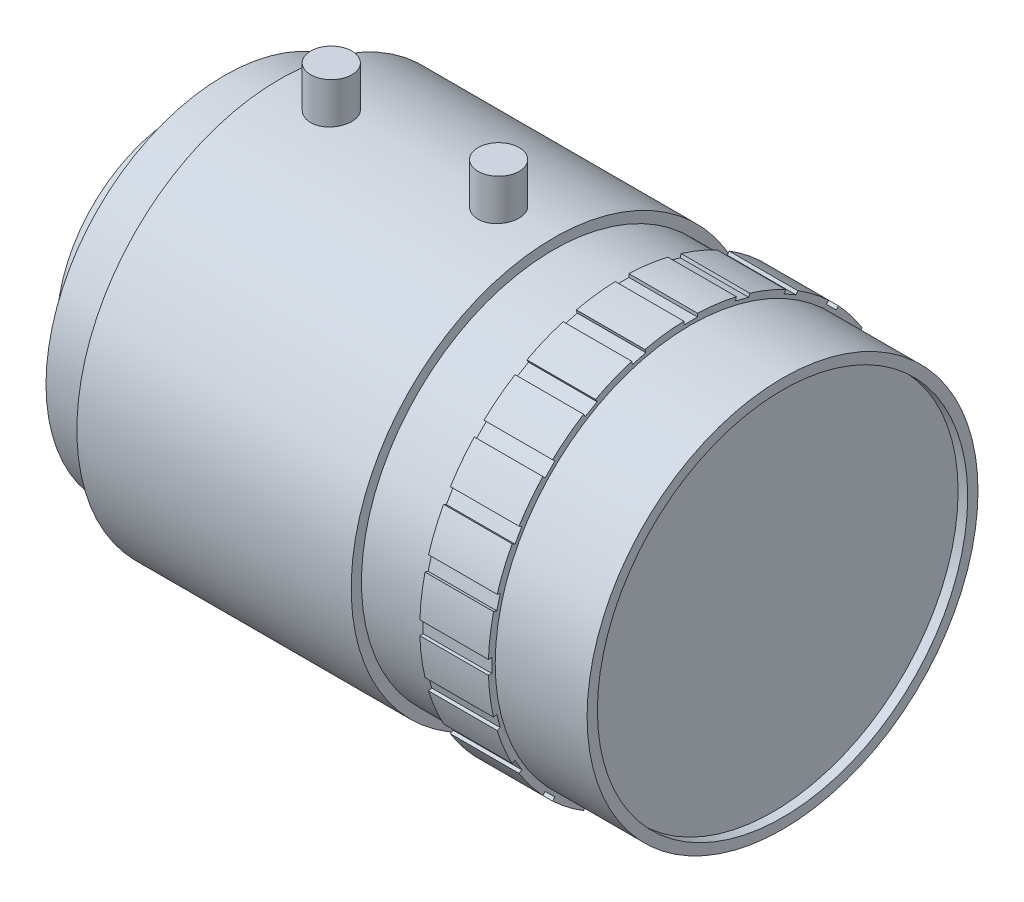
SolidWorks part; units mm, degrees
ref_plane "前视基准面" through (0, 0, 0) normal (0, 0, 1) x (1, 0, 0)
ref_plane "上视基准面" through (0, 0, 0) normal (0, 1, 0) x (1, 0, 0)
ref_plane "右视基准面" through (0, 0, 0) normal (1, 0, 0) x (0, 0, -1)
sketch "草图1" plane through (0, 0, 0) normal (1, 0, 0) x (0, 0, -1)
  circle A0 centre (0, 0) radius 14.75
  dimension "D1" = 29.5
extrude "凸台-拉伸1" add sketch "草图1" along normal blind 20
sketch "草图2" plane through (20, 0, 0) normal (1, 0, 0) x (0, 0, -1)
  circle A0 centre (0, 0) radius 14
  dimension "D1" = 28
extrude "凸台-拉伸2" add sketch "草图2" along normal blind 5
sketch "草图3" plane through (25, 0, 0) normal (1, 0, 0) x (0, 0, -1)
  circle A0 centre (0, 0) radius 14.75
extrude "凸台-拉伸3" add sketch "草图3" along normal blind 5
sketch "草图4" plane through (30, 0, 0) normal (1, 0, 0) x (0, 0, -1)
  circle A0 centre (0, 0) radius 14.25
  circle A1 centre (0, 0) radius 13.5
  dimension "D1" = 28.5
  dimension "D2" = 27
extrude "凸台-拉伸4" add sketch "草图4" along normal blind 6.7
sketch "草图5" plane through (30, 0, 0) normal (1, 0, 0) x (0, 0, -1)
  circle A1 centre (0, 0) radius 13.5
  circle A2 centre (0, 0) radius 13.5
  dimension "D1" = 0
extrude "凸台-拉伸5" add sketch "草图5" along normal blind 6
sketch "草图6" plane through (36, 0, 0) normal (1, 0, 0) x (0, 0, -1)
  line L1 (-0.5, 24.5486) -> (0.5, 24.5486)
  line L2 (-0.5, 24.5486) -> (-0.5, 14.5)
  line L3 (-0.5, 14.5) -> (0.5, 14.5)
  line L4 (0.5, 24.5486) -> (0.5, 14.5)
  line L5 (-0.5, 24.5486) -> (0.5, 14.5) construction
  line L6 (-0.5, 14.5) -> (0.5, 24.5486) construction
  point P0 (0, 19.5243)
  dimension "D1" = 1
  dimension "D2" = 0
  dimension "D3" = 14.5
extrude "切除-拉伸1" cut sketch "草图6" against normal blind 15
pattern_circular "阵列(圆周)1" count 24 every 15 about axis through (0, 0, 0) along (1, 0, 0) of "切除-拉伸1"
sketch "草图7" plane through (0, 0, 0) normal (0, 1, 0) x (1, 0, 0)
  circle A0 centre (3.8, 0) radius 1.5
  circle A1 centre (16, 0) radius 1.5
  dimension "D1" = 3.8
  dimension "D2" = 16
  dimension "D3" = 0
  dimension "D4" = 0
  dimension "D5" = 3
  dimension "D6" = 3
extrude "凸台-拉伸6" add sketch "草图7" along normal blind 17.7
sketch "草图8" plane through (0, 0, 0) normal (-1, 0, 0) x (0, 0, 1)
  circle A0 centre (0, 0) radius 10
  dimension "D1" = 20
extrude "凸台-拉伸7" add sketch "草图8" along normal blind 1
sketch "草图9" plane through (-1, 0, 0) normal (-1, 0, 0) x (0, 0, 1)
  circle A0 centre (0, 0) radius 13
  dimension "D1" = 26
extrude "凸台-拉伸8" add sketch "草图9" along normal blind 3
sketch "草图10" plane through (-4, 0, 0) normal (-1, 0, 0) x (0, 0, 1)
  circle A0 centre (0, 0) radius 8.9
  dimension "D1" = 17.8
extrude "凸台-拉伸9" add sketch "草图10" along normal blind 3.3
